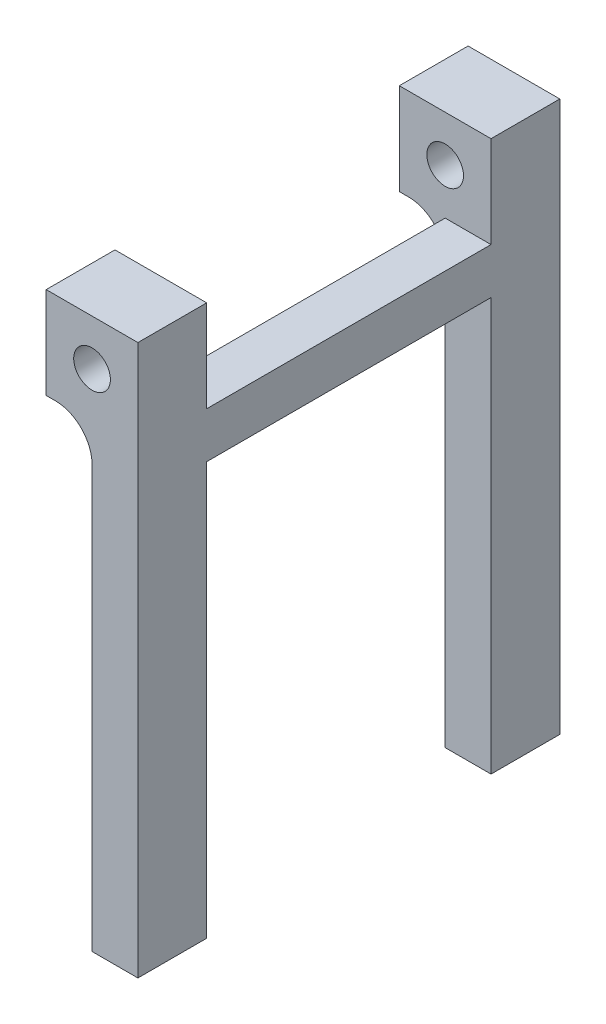
SolidWorks part; units mm, degrees
material "1060 合金"
ref_plane "前视基准面" through (0, 0, 0) normal (0, 0, 1) x (1, 0, 0)
ref_plane "上视基准面" through (0, 0, 0) normal (0, 1, 0) x (1, 0, 0)
ref_plane "右视基准面" through (0, 0, 0) normal (1, 0, 0) x (0, 0, -1)
sketch "草图3" plane through (0, 0, 0) normal (1, 0, 0) x (0, 0, -1)
  line L0 (0, 0) -> (0, 125.5508) construction
  line L1 (-85.8608, 0) -> (0, 0) construction
  line L2 (31, 0) -> (46, 0)
  line L3 (-46, 100) -> (46, 100)
  line L4 (-46, 100) -> (-46, 0)
  line L5 (-46, 0) -> (-31, 0)
  line L6 (46, 100) -> (46, 0)
  line L9 (31, 90) -> (-31, 90)
  line L10 (31, 90) -> (31, 0)
  line L12 (-31, 90) -> (-31, 0)
  line L15 (0, 0) -> (85.183, 0) construction
  dimension "D1" = 10
  dimension "D2" = 15
  dimension "D3" = 90
  dimension "D4" = 62
  dimension "D5" = 15
extrude "凸台-拉伸2" add sketch "草图3" along normal mid plane 10
sketch "草图5" plane through (0, 0, 46) normal (0, 0, 1) x (1, 0, 0)
  line L0 (-15, 110) -> (5, 110) construction
  line L1 (-15, 100) -> (5, 100)
  line L2 (-15, 100) -> (-15, 120)
  line L3 (-15, 120) -> (5, 120)
  line L4 (5, 100) -> (5, 120)
  line L5 (5, 100) -> (5, 0) construction
  line L7 (5, 110) -> (-5, 120) construction
  line L8 (-5, 120) -> (-5, 100) construction
  line L10 (5, 100) -> (-5, 100) construction
  circle A0 centre (-5, 110) radius 4
  dimension "D3" = 8
  dimension "D1" = 20
  dimension "D2" = 20
extrude "凸台-拉伸3" add sketch "草图5" against normal blind 15
mirror "镜向1" about plane through (0, 0, 0) normal (0, 0, 1) of "凸台-拉伸3"
fillet "圆角1" radius 8 2 edges at (-5, 100, -38.5)
move or copy body "实体-移动/复制1" [suppressed] bodies to move or copy 104
